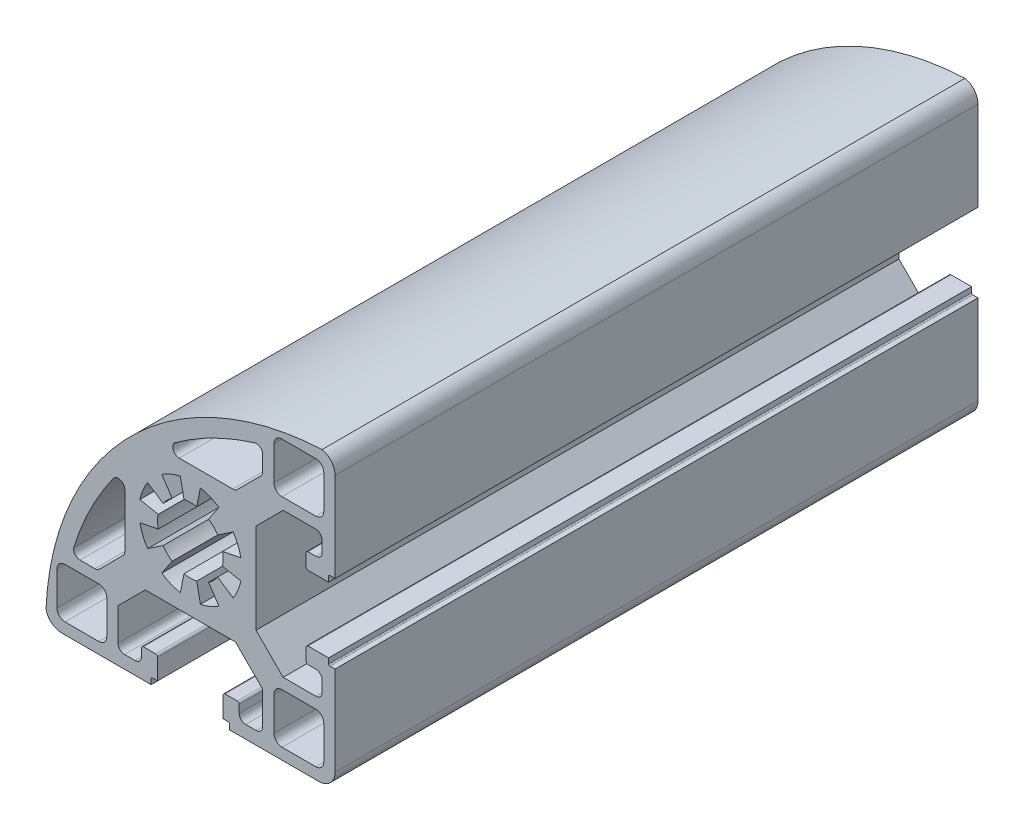
SolidWorks part; units mm, degrees
ref_plane "前视基准面" through (0, 0, 0) normal (0, 0, 1) x (1, 0, 0)
ref_plane "上视基准面" through (0, 0, 0) normal (0, 1, 0) x (1, 0, 0)
ref_plane "右视基准面" through (0, 0, 0) normal (1, 0, 0) x (0, 0, -1)
sketch "草图1" plane through (0, 0, 0) normal (0, 0, 1) x (1, 0, 0)
  line L0 (23.2056, 19.2658) -> (23.2056, 5.3658)
  line L1 (20.2056, 12.2658) -> (14.9556, 12.2658)
  line L2 (13.7056, 13.5158) -> (13.7056, 18.7658)
  line L3 (14.9556, 20.0158) -> (20.2056, 20.0158)
  line L4 (21.4556, 18.7658) -> (21.4556, 13.5158)
  line L5 (15.1376, 10.5158) -> (20.2056, 10.5158)
  line L6 (21.2056, 9.5158) -> (21.2056, 7.8658)
  line L7 (20.2056, 6.8658) -> (19.0056, 6.8658)
  line L8 (18.7056, 6.5658) -> (18.7056, 4.6658)
  line L9 (19.0056, 4.3658) -> (22.2056, 4.3658)
  line L10 (23.2056, 5.3658) -> (22.4056, 5.3658)
  line L11 (22.2056, 5.1658) -> (22.2056, 4.3658)
  line L12 (-5.3944, -23.2342) -> (-19.2944, -23.2342)
  line L13 (-4.3944, -22.2342) -> (-4.3944, -19.0342)
  line L14 (-4.6944, -18.7342) -> (-6.5944, -18.7342)
  line L15 (-6.8944, -19.0342) -> (-6.8944, -20.2342)
  line L16 (-7.8944, -21.2342) -> (-9.5444, -21.2342)
  line L17 (-10.5444, -20.2342) -> (-10.5444, -15.1662)
  line L18 (-18.7944, -13.7342) -> (-13.5444, -13.7342)
  line L19 (-12.2944, -14.9842) -> (-12.2944, -20.2342)
  line L20 (-13.5444, -21.4842) -> (-18.7944, -21.4842)
  line L21 (-20.0444, -20.2342) -> (-20.0444, -14.9842)
  line L22 (-4.3944, -22.2342) -> (-5.1944, -22.2342)
  line L23 (-5.3944, -22.4342) -> (-5.3944, -23.2342)
  line L24 (6.8056, -23.2342) -> (20.7056, -23.2342)
  line L25 (23.2056, -20.7342) -> (23.2056, -6.8342)
  line L26 (5.8056, -22.2342) -> (5.8056, -19.0342)
  line L27 (6.1056, -18.7342) -> (8.0056, -18.7342)
  line L28 (8.3056, -19.0342) -> (8.3056, -20.2342)
  line L29 (9.3056, -21.2342) -> (10.9556, -21.2342)
  line L30 (11.9556, -20.2342) -> (11.9556, -15.1662)
  line L31 (20.2056, -13.7342) -> (14.9556, -13.7342)
  line L32 (13.7056, -14.9842) -> (13.7056, -20.2342)
  line L33 (14.9556, -21.4842) -> (20.2056, -21.4842)
  line L34 (21.4556, -20.2342) -> (21.4556, -14.9842)
  line L35 (15.1376, -11.9842) -> (20.2056, -11.9842)
  line L36 (21.2056, -10.9842) -> (21.2056, -9.3342)
  line L37 (20.2056, -8.3342) -> (19.0056, -8.3342)
  line L38 (18.7056, -8.0342) -> (18.7056, -6.1342)
  line L39 (19.0056, -5.8342) -> (22.2056, -5.8342)
  line L40 (5.8056, -22.2342) -> (6.6056, -22.2342)
  line L41 (6.8056, -22.4342) -> (6.8056, -23.2342)
  line L42 (23.2056, -6.8342) -> (22.4056, -6.8342)
  line L43 (22.2056, -6.6342) -> (22.2056, -5.8342)
  line L44 (-3.7389, -7.386) -> (-2.1278, -4.9747)
  line L45 (-0.8551, -8.5805) -> (-0.2893, -5.7362)
  line L46 (2.2663, -8.5805) -> (1.7006, -5.7362)
  line L47 (5.1502, -7.386) -> (3.539, -4.9747)
  line L48 (7.3574, -5.1788) -> (4.9461, -3.5676)
  line L49 (8.5519, -2.2949) -> (5.7076, -1.7292)
  line L50 (8.5519, 0.8265) -> (5.7076, 0.2607)
  line L51 (7.3574, 3.7103) -> (4.9461, 2.0992)
  line L52 (5.1502, 5.9175) -> (3.539, 3.5063)
  line L53 (2.2663, 7.1121) -> (1.7006, 4.2678)
  line L54 (-0.8551, 7.1121) -> (-0.2893, 4.2678)
  line L55 (-3.7389, 5.9175) -> (-2.1278, 3.5063)
  line L56 (-5.9461, 3.7103) -> (-3.5349, 2.0992)
  line L57 (-7.1407, 0.8265) -> (-4.2964, 0.2607)
  line L58 (-7.1407, -2.2949) -> (-4.2964, -1.7292)
  line L59 (-5.9461, -5.1788) -> (-3.5349, -3.5676)
  line L60 (10.9056, -7.7522) -> (10.9056, 6.2838)
  line L61 (11.9556, 16.425) -> (11.9556, 14.112)
  line L62 (11.6627, 13.4049) -> (8.0165, 9.7587)
  line L63 (7.3094, 9.4658) -> (-1.0346, 9.4658)
  line L64 (-6.3124, -10.9342) -> (7.7236, -10.9342)
  line L65 (15.1376, 10.5158) -> (10.9056, 6.2838)
  line L66 (11.9556, -15.1662) -> (7.7236, -10.9342)
  line L67 (15.1376, -11.9842) -> (10.9056, -7.7522)
  line L68 (-16.4536, -11.9842) -> (-14.1406, -11.9842)
  line L69 (-13.4335, -11.6913) -> (-9.7873, -8.0451)
  line L70 (-9.4944, -7.338) -> (-9.4944, 1.006)
  line L71 (-10.5444, -15.1662) -> (-6.3124, -10.9342)
  arc A0 (-0.2893, -5.7362) -> (1.7006, -5.7362) centre (0.7056, -0.7342) ccw
  arc A1 (3.539, -4.9747) -> (4.9461, -3.5676) centre (0.7056, -0.7342) ccw
  arc A2 (5.7076, -1.7292) -> (5.7076, 0.2607) centre (0.7056, -0.7342) ccw
  arc A3 (4.9461, 2.0992) -> (3.539, 3.5063) centre (0.7056, -0.7342) ccw
  arc A4 (1.7006, 4.2678) -> (-0.2893, 4.2678) centre (0.7056, -0.7342) ccw
  arc A5 (-2.1278, 3.5063) -> (-3.5349, 2.0992) centre (0.7056, -0.7342) ccw
  arc A6 (-4.2964, 0.2607) -> (-4.2964, -1.7292) centre (0.7056, -0.7342) ccw
  arc A7 (-3.5349, -3.5676) -> (-2.1278, -4.9747) centre (0.7056, -0.7342) ccw
  arc A8 (-3.7389, -7.386) -> (-0.8551, -8.5805) centre (0.7056, -0.7342) ccw
  arc A9 (2.2663, -8.5805) -> (5.1502, -7.386) centre (0.7056, -0.7342) ccw
  arc A10 (7.3574, -5.1788) -> (8.5519, -2.2949) centre (0.7056, -0.7342) ccw
  arc A11 (8.5519, 0.8265) -> (7.3574, 3.7103) centre (0.7056, -0.7342) ccw
  arc A12 (5.1502, 5.9175) -> (2.2663, 7.1121) centre (0.7056, -0.7342) ccw
  arc A13 (-0.8551, 7.1121) -> (-3.7389, 5.9175) centre (0.7056, -0.7342) ccw
  arc A14 (-5.9461, 3.7103) -> (-7.1407, 0.8265) centre (0.7056, -0.7342) ccw
  arc A15 (-7.1407, -2.2949) -> (-5.9461, -5.1788) centre (0.7056, -0.7342) ccw
  arc A16 (23.2056, 19.2658) -> (21.1808, 21.7202) centre (20.7056, 19.2658) ccw
  arc A17 (13.7056, 13.5158) -> (14.9556, 12.2658) centre (14.9556, 13.5158) ccw
  arc A18 (14.9556, 20.0158) -> (13.7056, 18.7658) centre (14.9556, 18.7658) ccw
  arc A19 (21.4556, 18.7658) -> (20.2056, 20.0158) centre (20.2056, 18.7658) ccw
  arc A20 (20.2056, 12.2658) -> (21.4556, 13.5158) centre (20.2056, 13.5158) ccw
  arc A21 (21.2056, 9.5158) -> (20.2056, 10.5158) centre (20.2056, 9.5158) ccw
  arc A22 (20.2056, 6.8658) -> (21.2056, 7.8658) centre (20.2056, 7.8658) ccw
  arc A23 (19.0056, 6.8658) -> (18.7056, 6.5658) centre (19.0056, 6.5658) ccw
  arc A24 (18.7056, 4.6658) -> (19.0056, 4.3658) centre (19.0056, 4.6658) ccw
  arc A25 (22.4056, 5.3658) -> (22.2056, 5.1658) centre (22.4056, 5.1658) ccw
  arc A26 (-21.7488, -21.2094) -> (-19.2944, -23.2342) centre (-19.2944, -20.7342) ccw
  arc A27 (-4.3944, -19.0342) -> (-4.6944, -18.7342) centre (-4.6944, -19.0342) ccw
  arc A28 (-6.5944, -18.7342) -> (-6.8944, -19.0342) centre (-6.5944, -19.0342) ccw
  arc A29 (-7.8944, -21.2342) -> (-6.8944, -20.2342) centre (-7.8944, -20.2342) ccw
  arc A30 (-10.5444, -20.2342) -> (-9.5444, -21.2342) centre (-9.5444, -20.2342) ccw
  arc A31 (-12.2944, -14.9842) -> (-13.5444, -13.7342) centre (-13.5444, -14.9842) ccw
  arc A32 (-13.5444, -21.4842) -> (-12.2944, -20.2342) centre (-13.5444, -20.2342) ccw
  arc A33 (-20.0444, -20.2342) -> (-18.7944, -21.4842) centre (-18.7944, -20.2342) ccw
  arc A34 (-18.7944, -13.7342) -> (-20.0444, -14.9842) centre (-18.7944, -14.9842) ccw
  arc A35 (-5.1944, -22.2342) -> (-5.3944, -22.4342) centre (-5.1944, -22.4342) ccw
  arc A36 (20.7056, -23.2342) -> (23.2056, -20.7342) centre (20.7056, -20.7342) ccw
  arc A37 (6.1056, -18.7342) -> (5.8056, -19.0342) centre (6.1056, -19.0342) ccw
  arc A38 (8.3056, -19.0342) -> (8.0056, -18.7342) centre (8.0056, -19.0342) ccw
  arc A39 (8.3056, -20.2342) -> (9.3056, -21.2342) centre (9.3056, -20.2342) ccw
  arc A40 (10.9556, -21.2342) -> (11.9556, -20.2342) centre (10.9556, -20.2342) ccw
  arc A41 (14.9556, -13.7342) -> (13.7056, -14.9842) centre (14.9556, -14.9842) ccw
  arc A42 (13.7056, -20.2342) -> (14.9556, -21.4842) centre (14.9556, -20.2342) ccw
  arc A43 (20.2056, -21.4842) -> (21.4556, -20.2342) centre (20.2056, -20.2342) ccw
  arc A44 (21.4556, -14.9842) -> (20.2056, -13.7342) centre (20.2056, -14.9842) ccw
  arc A45 (20.2056, -11.9842) -> (21.2056, -10.9842) centre (20.2056, -10.9842) ccw
  arc A46 (21.2056, -9.3342) -> (20.2056, -8.3342) centre (20.2056, -9.3342) ccw
  arc A47 (18.7056, -8.0342) -> (19.0056, -8.3342) centre (19.0056, -8.0342) ccw
  arc A48 (19.0056, -5.8342) -> (18.7056, -6.1342) centre (19.0056, -6.1342) ccw
  arc A49 (6.8056, -22.4342) -> (6.6056, -22.2342) centre (6.6056, -22.4342) ccw
  arc A50 (22.2056, -6.6342) -> (22.4056, -6.8342) centre (22.4056, -6.6342) ccw
  arc A51 (11.6627, 13.4049) -> (11.9556, 14.112) centre (10.9556, 14.112) ccw
  arc A52 (7.3094, 9.4658) -> (8.0165, 9.7587) centre (7.3094, 10.4658) ccw
  arc A53 (21.1808, 21.7202) -> (-21.7488, -21.2094) centre (23.2056, -23.2342) ccw
  arc A54 (10.7853, 17.4104) -> (-1.7398, 11.1747) centre (23.2056, -23.2342) ccw
  arc A55 (-1.7398, 11.1747) -> (-1.0346, 9.4658) centre (-1.0346, 10.4658) ccw
  arc A56 (11.9556, 16.425) -> (10.7853, 17.4104) centre (10.9556, 16.425) ccw
  arc A57 (-14.1406, -11.9842) -> (-13.4335, -11.6913) centre (-14.1406, -10.9842) ccw
  arc A58 (-9.7873, -8.0451) -> (-9.4944, -7.338) centre (-10.4944, -7.338) ccw
  arc A59 (-11.2033, 1.7112) -> (-17.439, -10.8139) centre (23.2056, -23.2342) ccw
  arc A60 (-9.4944, 1.006) -> (-11.2033, 1.7112) centre (-10.4944, 1.006) ccw
  arc A61 (-17.439, -10.8139) -> (-16.4536, -11.9842) centre (-16.4536, -10.9842) ccw
extrude "凸台-拉伸1" add sketch "草图1" along normal blind 100
